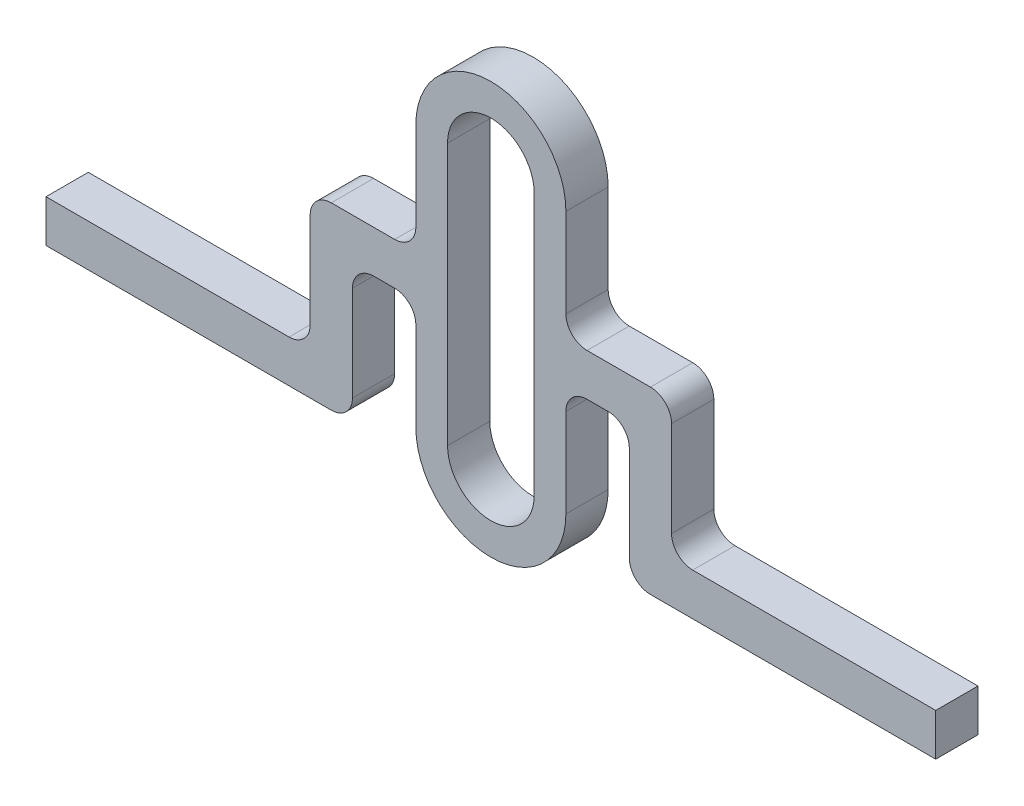
SolidWorks part; units mm, degrees
ref_plane "Front Plane" through (0, 0, 0) normal (0, 0, 1) x (1, 0, 0)
ref_plane "Top Plane" through (0, 0, 0) normal (0, 1, 0) x (1, 0, 0)
ref_plane "Right Plane" through (0, 0, 0) normal (1, 0, 0) x (0, 0, -1)
sketch "Sketch1" plane through (0, 0, 0) normal (0, 0, 1) x (1, 0, 0)
  line L0 (0, -12.4) -> (0, 12.4) construction
  line L1 (-4.1, -12.4) -> (-4.1, 12.4)
  line L2 (4.1, -12.4) -> (4.1, 12.4)
  line L3 (-7.1, -12.4) -> (-7.1, 12.4)
  line L4 (7.1, -12.4) -> (7.1, 12.4)
  arc A0 (-4.1, -12.4) -> (4.1, -12.4) centre (0, -12.4) ccw
  arc A1 (4.1, 12.4) -> (-4.1, 12.4) centre (0, 12.4) ccw
  arc A2 (7.1, 12.4) -> (-7.1, 12.4) centre (0, 12.4) ccw
  arc A3 (-7.1, -12.4) -> (7.1, -12.4) centre (0, -12.4) ccw
  point P2 (0, 0)
  point P8 (0, 16.5)
  point P9 (0, -16.5)
  dimension "D1" = 33
  dimension "D2" = 8.2
  dimension "D3" = 3
extrude "Boss-Extrude1" add sketch "Sketch1" along normal mid plane 4
sketch "Sketch2" plane through (7.1, 0, 0) normal (1, 0, 0) x (0, 0, -1)
  line L0 (2, -12.4) -> (2, 12.4) construction
  line L1 (-2, -2) -> (2, -2)
  line L2 (-2, -2) -> (-2, 2)
  line L3 (-2, 2) -> (2, 2)
  line L4 (2, -2) -> (2, 2)
  line L5 (-2, -2) -> (2, 2) construction
  line L6 (-2, 2) -> (2, -2) construction
  point P0 (0, 0)
extrude "Boss-Extrude2" add sketch "Sketch2" along normal blind 10
sketch "Sketch4" plane through (0, -2, 0) normal (0, -1, 0) x (1, 0, 0)
  line L0 (17.1, -2) -> (7.1, -2) construction
  line L1 (17.1, 2) -> (13.1, 2)
  line L2 (17.1, 2) -> (17.1, -2)
  line L3 (17.1, -2) -> (13.1, -2)
  line L4 (13.1, 2) -> (13.1, -2)
extrude "Boss-Extrude4" add sketch "Sketch4" along normal blind 13
sketch "Sketch5" plane through (17.1, 0, 0) normal (1, 0, 0) x (0, 0, -1)
  line L0 (2, -15) -> (2, 2) construction
  line L1 (-2, -15) -> (2, -15)
  line L2 (-2, -15) -> (-2, -11)
  line L3 (-2, -11) -> (2, -11)
  line L4 (2, -15) -> (2, -11)
extrude "Boss-Extrude5" add sketch "Sketch5" along normal blind 25
mirror "Mirror2" about plane through (0, 0, 0) normal (1, 0, 0) of "Boss-Extrude5", "Boss-Extrude4", "Boss-Extrude2"
fillet "Fillet2" radius 2 12 edges at (-17.1, -11, 0) (-13.1, -2, 0) (-7.1, -2, 0) (-7.1, 2, 0) (17.1, -11, 0) (13.1, -2, 0) (7.1, -2, 0) (7.1, 2, 0) (-13.1, -15, 0) (17.1, 2, 0) (13.1, -15, 0) (-17.1, 2, 0)
